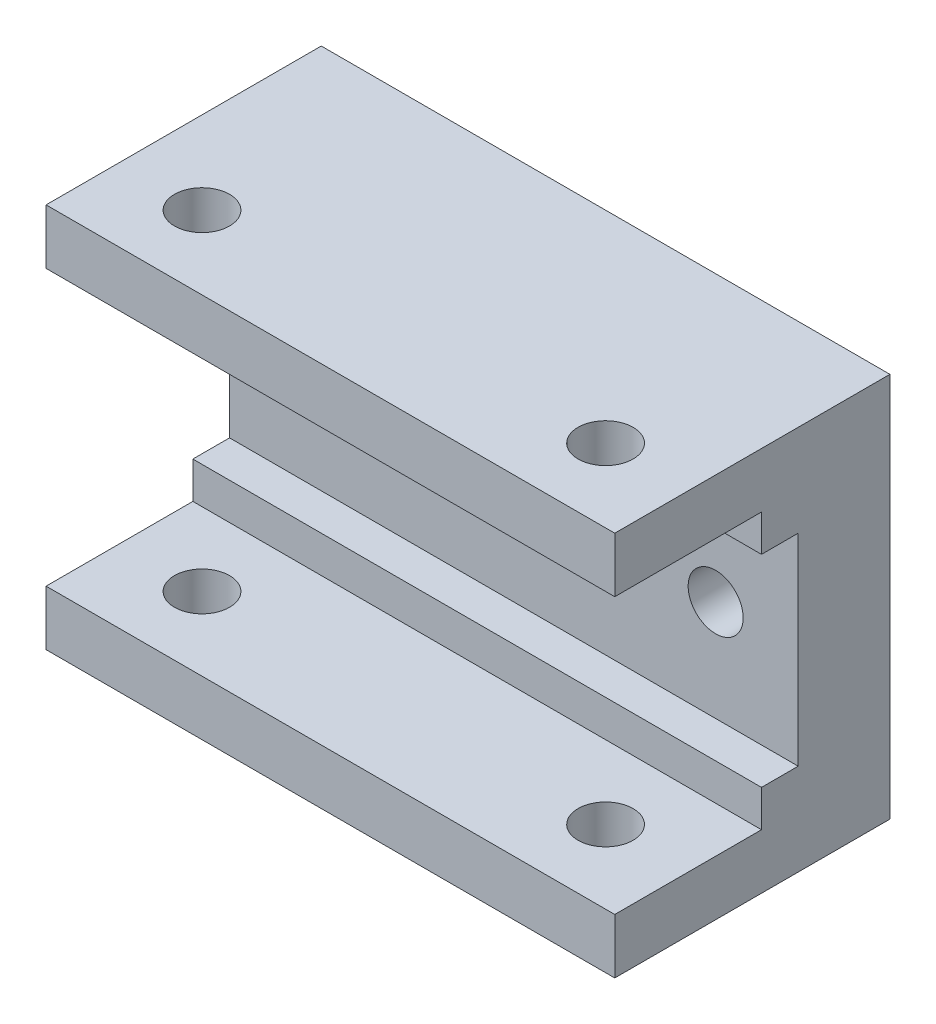
SolidWorks part; units mm, degrees
material "POM 乙缩醛共聚物"
ref_plane "前视基准面" through (0, 0, 0) normal (0, 0, 1) x (1, 0, 0)
ref_plane "上视基准面" through (0, 0, 0) normal (0, 1, 0) x (1, 0, 0)
ref_plane "右视基准面" through (0, 0, 0) normal (1, 0, 0) x (0, 0, -1)
sketch "草图1" plane through (0, 0, 0) normal (0, 0, 1) x (1, 0, 0)
  line L1 (-15.5, 10.5) -> (15.5, 10.5)
  line L2 (-15.5, 10.5) -> (-15.5, -10.5)
  line L3 (-15.5, -10.5) -> (15.5, -10.5)
  line L4 (15.5, 10.5) -> (15.5, -10.5)
  line L5 (-15.5, 10.5) -> (15.5, -10.5) construction
  line L6 (-15.5, -10.5) -> (15.5, 10.5) construction
  point P0 (0, 0)
  dimension "D1" = 21
  dimension "D2" = 31
extrude "凸台-拉伸1" add sketch "草图1" along normal blind 5
sketch "草图2" plane through (0, 0, 5) normal (0, 0, 1) x (1, 0, 0)
  line L0 (15.5, -10.5) -> (15.5, 10.5) construction
  line L1 (-15.5, 10.5) -> (15.5, 10.5)
  line L2 (-15.5, 10.5) -> (-15.5, 7.5)
  line L3 (-15.5, 7.5) -> (15.5, 7.5)
  line L4 (15.5, 10.5) -> (15.5, 7.5)
  line L6 (-15.5, -10.5) -> (15.5, -10.5)
  line L7 (-15.5, -10.5) -> (-15.5, -7.5)
  line L8 (-15.5, -7.5) -> (15.5, -7.5)
  line L9 (15.5, -10.5) -> (15.5, -7.5)
  dimension "D1" = 3
  dimension "D2" = 3
extrude "凸台-拉伸2" add sketch "草图2" along normal blind 10
sketch "草图5" plane through (0, 10.5, 0) normal (0, 1, 0) x (1, 0, 0)
  line L0 (-15.5, -11) -> (15.5, -11) construction
  line L1 (-15.5, -15) -> (-15.5, 0) construction
  line L2 (15.5, -15) -> (15.5, 0) construction
  line L3 (15.5, -15) -> (-15.5, -15) construction
  line L4 (0, -11) -> (0, -15) construction
  circle A1 centre (11, -11) radius 1.5
  circle A2 centre (-11, -11) radius 1.5
  dimension "D2" = 3
  dimension "D1" = 4
  dimension "D3" = 11
extrude "切除-拉伸2" cut sketch "草图5" against normal through all
sketch "草图6" plane through (0, 0, 0) normal (0, 0, -1) x (-1, 0, 0)
  line L0 (-15.5, 0) -> (15.5, 0) construction
  line L1 (-15.5, -10.5) -> (-15.5, 10.5) construction
  line L2 (15.5, 10.5) -> (15.5, -10.5) construction
  line L3 (0, 10.5) -> (0, 0) construction
  line L4 (-15.5, 10.5) -> (15.5, 10.5) construction
  circle A0 centre (-11, 0) radius 1.5
  circle A1 centre (11, 0) radius 1.5
  dimension "D1" = 3
  dimension "D2" = 11
extrude "切除-拉伸3" cut sketch "草图6" against normal through all
sketch "草图7" plane through (0, 0, 5) normal (0, 0, 1) x (1, 0, 0)
  line L0 (-15.5, 0) -> (15.5, 0) construction
  line L1 (-15.5, 7.5) -> (-15.5, -7.5) construction
  line L2 (15.5, -7.5) -> (15.5, 7.5) construction
  line L3 (-15.5, -5.5) -> (15.5, -5.5)
  line L4 (-15.5, 7.5) -> (15.5, 7.5)
  line L5 (-15.5, 7.5) -> (-15.5, 5.5)
  line L6 (-15.5, 5.5) -> (15.5, 5.5)
  line L7 (15.5, 7.5) -> (15.5, 5.5)
  line L8 (15.5, -7.5) -> (15.5, -5.5)
  line L9 (-15.5, -7.5) -> (15.5, -7.5)
  line L10 (-15.5, -7.5) -> (-15.5, -5.5)
  dimension "D1" = 2
extrude "凸台-拉伸3" add sketch "草图7" along normal blind 2
